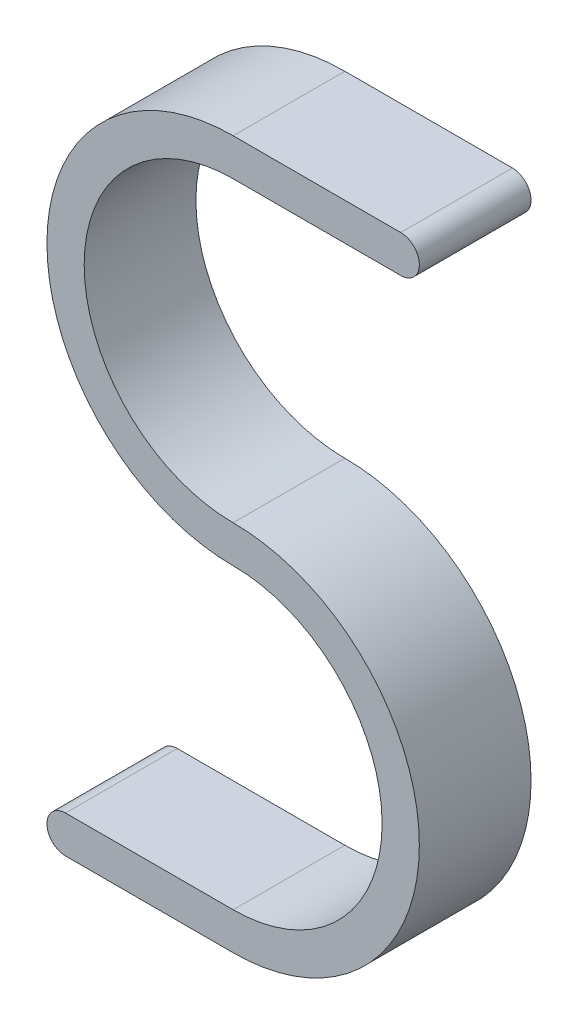
SolidWorks part; units mm, degrees
ref_plane "Front Plane" through (0, 0, 0) normal (0, 0, 1) x (1, 0, 0)
ref_plane "Top Plane" through (0, 0, 0) normal (0, 1, 0) x (1, 0, 0)
ref_plane "Right Plane" through (0, 0, 0) normal (1, 0, 0) x (0, 0, -1)
sketch "Sketch1" plane through (0, 0, 0) normal (0, 0, 1) x (1, 0, 0)
  line L0 (0, 0) -> (0, 100000) construction
  line L1 (0, 0) -> (100000, 0) construction
  line L2 (0, 2.5) -> (-22.5, 2.5)
  line L3 (-22.5, -87.5) -> (-45, -87.5)
  line L4 (0, -2.5) -> (-22.5, -2.5)
  line L5 (-22.5, -92.5) -> (-45, -92.5)
  arc A0 (0, -2.5) -> (0, 2.5) centre (0, 0) ccw
  arc A1 (-22.5, 2.5) -> (-22.5, -47.5) centre (-22.5, -22.5) ccw
  arc A2 (-22.5, -47.5) -> (-22.5, -87.5) centre (-22.5, -67.5) cw
  arc A3 (-22.5, -2.5) -> (-22.5, -42.5) centre (-22.5, -22.5) ccw
  arc A4 (-22.5, -42.5) -> (-22.5, -92.5) centre (-22.5, -67.5) cw
  arc A5 (-45, -87.5) -> (-45, -92.5) centre (-45, -90) ccw
  dimension "D1" = 5
  dimension "D2" = 22.5
  dimension "D3" = 25
  dimension "D4" = 20
  dimension "D7" = 20
  dimension "D8" = 25
  dimension "D10" = 50
  dimension "D5" = 22.5
  dimension "D6" = 22.5
  dimension "D9" = 22.5
extrude "Boss-Extrude1" add sketch "Sketch1" along normal blind 15
